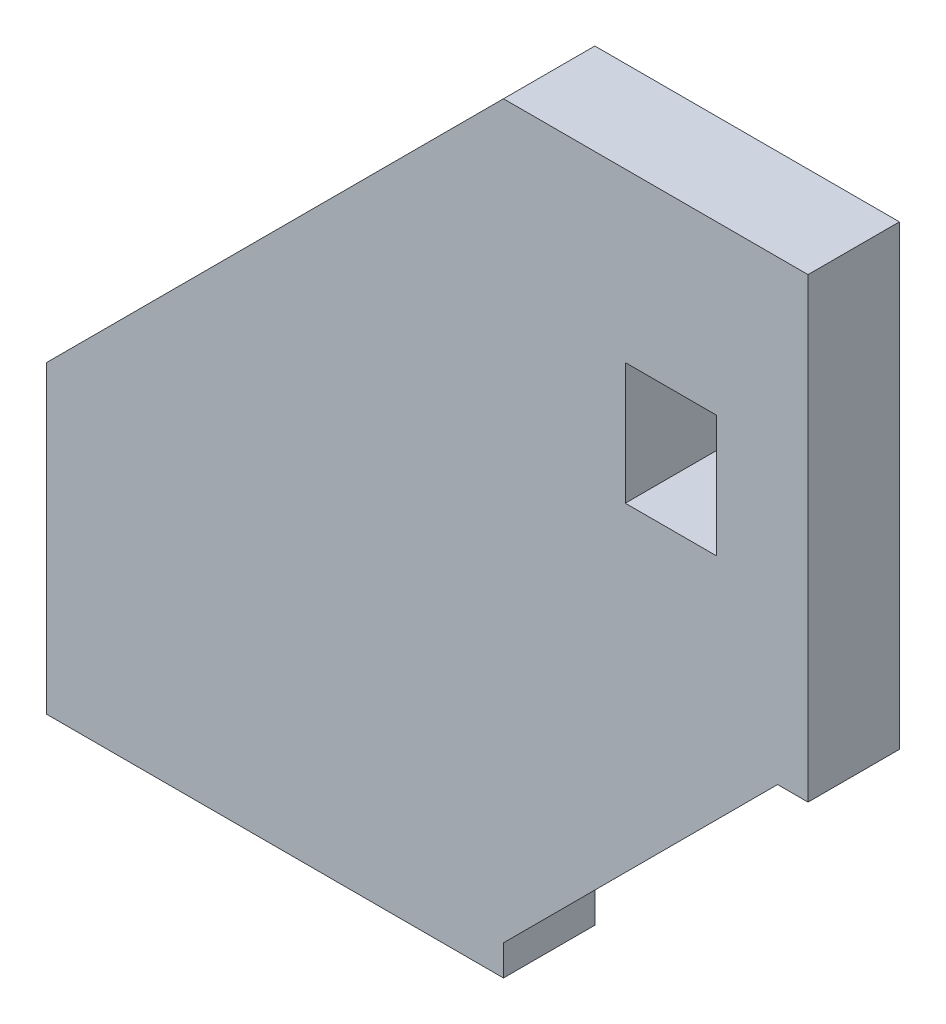
SolidWorks part; units mm, degrees
material "PBT General Purpose"
ref_plane "Front Plane" through (0, 0, 0) normal (0, 0, 1) x (1, 0, 0)
ref_plane "Top Plane" through (0, 0, 0) normal (0, 1, 0) x (1, 0, 0)
ref_plane "Right Plane" through (0, 0, 0) normal (1, 0, 0) x (0, 0, -1)
sketch "Sketch1" plane through (0, 0, 0) normal (0, 0, 1) x (1, 0, 0)
  line L0 (0, 0) -> (0, 1.5)
  line L3 (-2.5, -1) -> (-1, -1)
  line L7 (0, 1.5) -> (-1, 1.5)
  line L8 (-1, 1.5) -> (-2.5, 0)
  line L9 (-2.5, 0) -> (-2.5, -1)
  line L10 (0, 0) -> (-0.1, 0)
  line L11 (-0.1, 0) -> (-1, -0.9)
  line L12 (-1, -0.9) -> (-1, -1)
  dimension "D1" = 1.5
  dimension "D2" = 1
  dimension "D3" = 1
  dimension "D4" = 1.5
  dimension "D5" = 1
  dimension "D6" = 1
  dimension "D7" = 0.1
  dimension "D8" = 0.1
extrude "Boss-Extrude1" add sketch "Sketch1" along normal mid plane 0.3
sketch "Sketch2" plane through (0, 0, 0.15) normal (0, 0, 1) x (1, 0, 0)
  line L0 (0, 0) -> (0, 1.5) construction
  line L1 (-0.3, 0.95) -> (-0.6, 0.95)
  line L2 (-0.3, 0.95) -> (-0.3, 0.55)
  line L3 (-0.3, 0.55) -> (-0.6, 0.55)
  line L4 (-0.6, 0.95) -> (-0.6, 0.55)
  point P4 (-0.3, 0.75)
  point P7 (0, 0.75)
  dimension "D1" = 0.4
  dimension "D2" = 0.3
  dimension "D3" = 0.3
extrude "Cut-Extrude1" cut sketch "Sketch2" against normal through all
equation "\"t\"= 0.3'thickness of the sheets"
equation "\"FlexJoint\"= 0.15'Width of flextures"
equation "\"FoldJoint\"= 0.4'Width of folding joints"
equation "\"AssembleAngle\"= 90'Angle of assembly parts"
equation "\"D1@Boss-Extrude1\"=\"t\""
